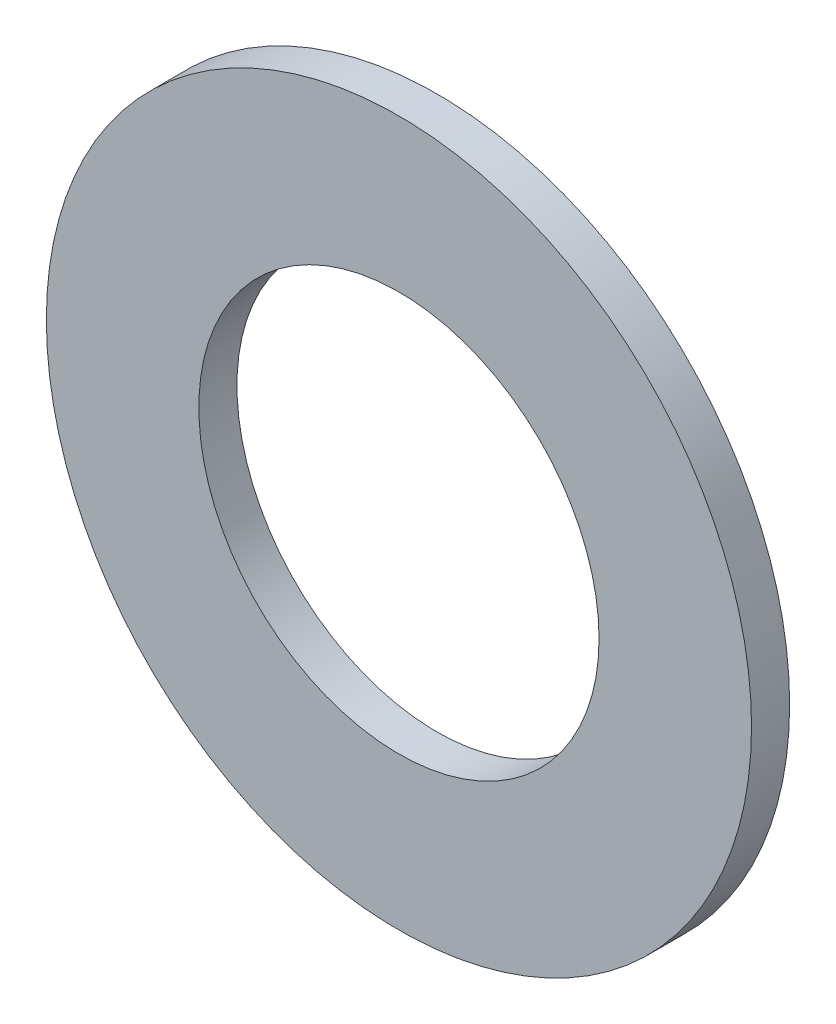
SolidWorks part; units mm, degrees
ref_plane "Front Plane" through (0, 0, 0) normal (0, 0, 1) x (1, 0, 0)
ref_plane "Top Plane" through (0, 0, 0) normal (0, 1, 0) x (1, 0, 0)
ref_plane "Right Plane" through (0, 0, 0) normal (1, 0, 0) x (0, 0, -1)
sketch "Sketch1" plane through (0, 0, 0) normal (0, 0, 1) x (1, 0, 0)
  circle A0 centre (0, 0) radius 2.1
  circle A1 centre (0, 0) radius 3.7
  dimension "ID" = 4.2
  dimension "OD" = 1.6
extrude "Boss-Extrude1" add sketch "Sketch1" along normal blind 0.4
equation "\"ID\"= 4.2"
equation "\"Width\"= 1.6"
equation "\"Spacer Thickness\"= 0.4"
equation "\"ID@Sketch1\"= \"ID\""
equation "\"OD@Sketch1\"= \"Width\""
equation "\"D1@Boss-Extrude1\"= \"Spacer Thickness\""
